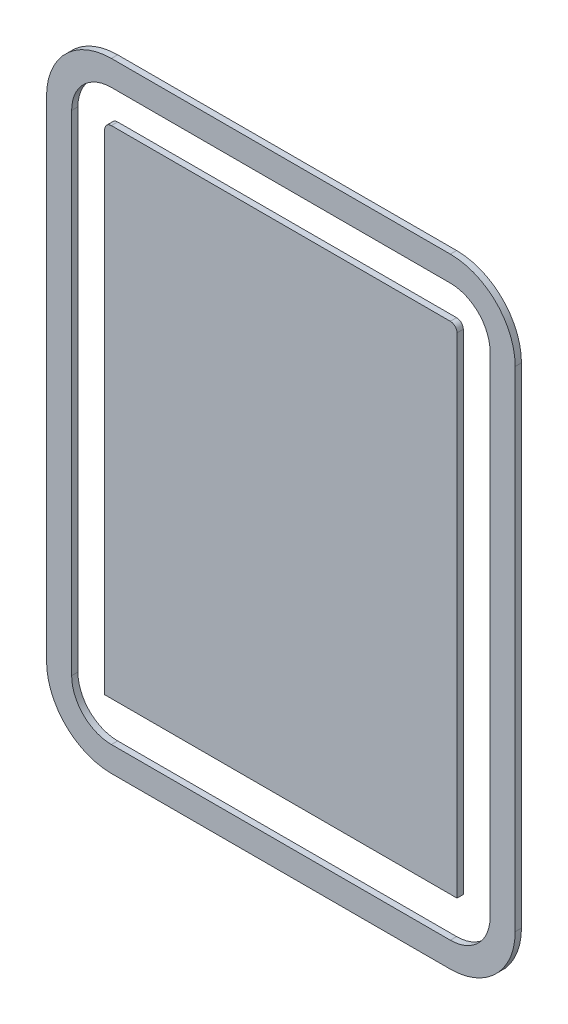
SolidWorks part; units mm, degrees
ref_plane "Front Plane" through (0, 0, 0) normal (0, 0, 1) x (1, 0, 0)
ref_plane "Top Plane" through (0, 0, 0) normal (0, 1, 0) x (1, 0, 0)
ref_plane "Right Plane" through (0, 0, 0) normal (1, 0, 0) x (0, 0, -1)
sketch "Sketch1" plane through (0, 0, 0) normal (0, 0, 1) x (1, 0, 0)
  line L8 (-61.5233, -81.5291) -> (22.6767, -81.5291)
  line L11 (22.6767, -81.5291) -> (22.6767, 35.4709)
  line L12 (-61.5233, 35.4709) -> (-61.5233, -81.5291)
  line L13 (21.0767, 37.0709) -> (-59.9233, 37.0709)
  line L14 (22.6767, -81.5291) -> (22.6767, 35.4709)
  line L15 (-61.5233, 35.4709) -> (-61.5233, -81.5291)
  line L16 (21.0767, 37.0709) -> (-59.9233, 37.0709)
  line L30 (30.5767, -81.5291) -> (30.5767, 35.4709)
  line L31 (-59.9233, -97.0291) -> (21.0767, -97.0291)
  line L32 (36.5767, -81.5291) -> (36.5767, 35.4709)
  line L33 (-75.4233, 35.4709) -> (-75.4233, -81.5291)
  line L34 (21.0767, 50.9709) -> (-59.9233, 50.9709)
  line L35 (-59.9233, -97.0291) -> (21.0767, -97.0291)
  line L36 (36.5767, -81.5291) -> (36.5767, 35.4709)
  line L37 (-75.4233, 35.4709) -> (-75.4233, -81.5291)
  line L38 (21.0767, 50.9709) -> (-59.9233, 50.9709)
  line L39 (-59.9233, -91.0291) -> (21.0767, -91.0291)
  line L40 (-69.4233, 35.4709) -> (-69.4233, -81.5291)
  line L41 (21.0767, 44.9709) -> (-59.9233, 44.9709)
  line L42 (30.5767, -81.5291) -> (30.5767, 35.4709)
  line L43 (-59.9233, -91.0291) -> (21.0767, -91.0291)
  line L44 (-69.4233, 35.4709) -> (-69.4233, -81.5291)
  line L45 (21.0767, 44.9709) -> (-59.9233, 44.9709)
  arc A9 (22.6767, 35.4709) -> (21.0767, 37.0709) centre (21.0767, 35.4709) ccw
  arc A10 (-59.9233, 37.0709) -> (-61.5233, 35.4709) centre (-59.9233, 35.4709) ccw
  arc A11 (22.6767, 35.4709) -> (21.0767, 37.0709) centre (21.0767, 35.4709) ccw
  arc A12 (-59.9233, 37.0709) -> (-61.5233, 35.4709) centre (-59.9233, 35.4709) ccw
  arc A20 (-75.4233, -81.5291) -> (-59.9233, -97.0291) centre (-59.9233, -81.5291) ccw
  arc A21 (21.0767, -97.0291) -> (36.5767, -81.5291) centre (21.0767, -81.5291) ccw
  arc A22 (36.5767, 35.4709) -> (21.0767, 50.9709) centre (21.0767, 35.4709) ccw
  arc A23 (-59.9233, 50.9709) -> (-75.4233, 35.4709) centre (-59.9233, 35.4709) ccw
  arc A24 (-75.4233, -81.5291) -> (-59.9233, -97.0291) centre (-59.9233, -81.5291) ccw
  arc A25 (21.0767, -97.0291) -> (36.5767, -81.5291) centre (21.0767, -81.5291) ccw
  arc A26 (36.5767, 35.4709) -> (21.0767, 50.9709) centre (21.0767, 35.4709) ccw
  arc A27 (-59.9233, 50.9709) -> (-75.4233, 35.4709) centre (-59.9233, 35.4709) ccw
  arc A28 (30.5767, 35.4709) -> (21.0767, 44.9709) centre (21.0767, 35.4709) ccw
  arc A29 (21.0767, -91.0291) -> (30.5767, -81.5291) centre (21.0767, -81.5291) ccw
  arc A30 (-69.4233, -81.5291) -> (-59.9233, -91.0291) centre (-59.9233, -81.5291) ccw
  arc A31 (-59.9233, 44.9709) -> (-69.4233, 35.4709) centre (-59.9233, 35.4709) ccw
  arc A32 (30.5767, 35.4709) -> (21.0767, 44.9709) centre (21.0767, 35.4709) ccw
  arc A33 (21.0767, -91.0291) -> (30.5767, -81.5291) centre (21.0767, -81.5291) ccw
  arc A34 (-69.4233, -81.5291) -> (-59.9233, -91.0291) centre (-59.9233, -81.5291) ccw
  arc A35 (-59.9233, 44.9709) -> (-69.4233, 35.4709) centre (-59.9233, 35.4709) ccw
  dimension "D1" = 8
  dimension "D2" = 2
  dimension "D3" = 3
extrude "Boss-Extrude1" add sketch "Sketch1" along normal blind 1.5
